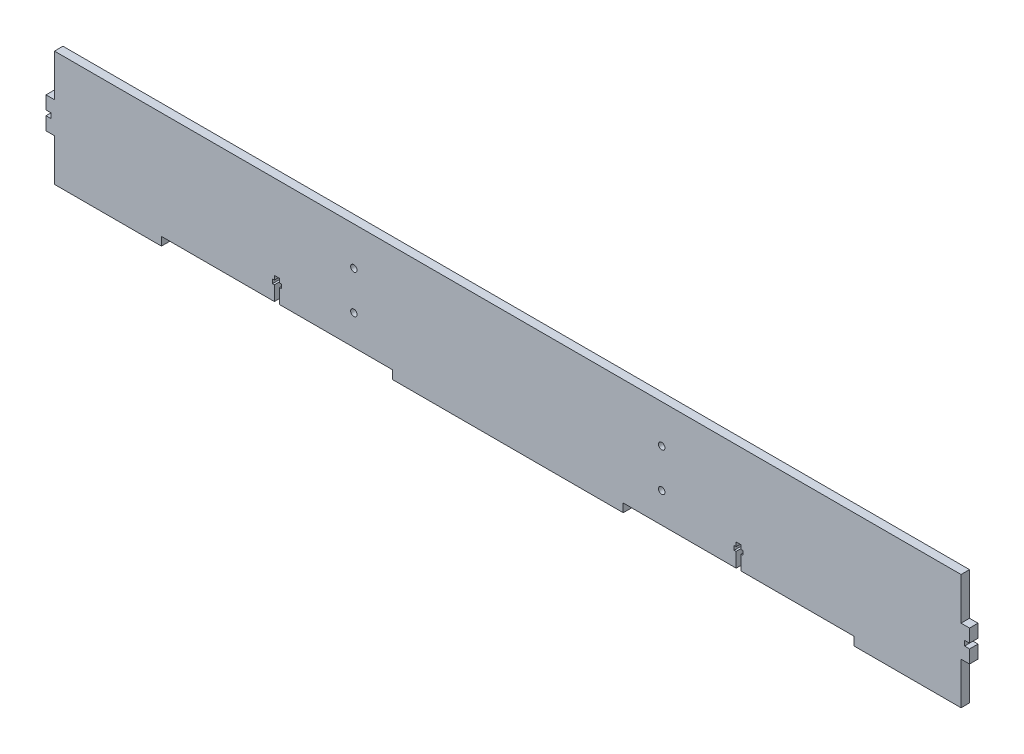
SolidWorks part; units mm, degrees
ref_plane "Front Plane" through (0, 0, 0) normal (0, 0, 1) x (1, 0, 0)
ref_plane "Top Plane" through (0, 0, 0) normal (0, 1, 0) x (1, 0, 0)
ref_plane "Right Plane" through (0, 0, 0) normal (1, 0, 0) x (0, 0, -1)
sketch "Sketch1" plane through (0, 0, 0) normal (0, 0, 1) x (1, 0, 0)
  line L0 (308.5, 78) -> (308.5, 50.625)
  line L1 (308.5, 50.625) -> (303, 50.625)
  line L2 (303, 50.625) -> (303, 42.125)
  line L3 (303, 42.125) -> (306.25, 42.125)
  line L4 (306.25, 42.125) -> (306.25, 40.5)
  line L5 (306.25, 40.5) -> (306.25, 38.875)
  line L6 (306.25, 38.875) -> (303, 38.875)
  line L7 (303, 38.875) -> (303, 30.375)
  line L8 (303, 30.375) -> (308.5, 30.375)
  line L9 (308.5, 30.375) -> (308.5, 3)
  line L10 (308.5, 3) -> (378, 3)
  line L11 (378, 3) -> (378, 8.5)
  line L12 (378, 8.5) -> (451.375, 8.5)
  line L13 (451.375, 8.5) -> (451.375, 17.95)
  line L14 (451.375, 17.95) -> (450.125, 17.95)
  line L15 (450.125, 17.95) -> (450.125, 20.6)
  line L16 (450.125, 20.6) -> (451.375, 20.6)
  line L17 (451.375, 20.6) -> (451.375, 23.25)
  line L18 (451.375, 23.25) -> (454.625, 23.25)
  line L19 (454.625, 23.25) -> (454.625, 20.6)
  line L20 (454.625, 20.6) -> (455.875, 20.6)
  line L21 (455.875, 20.6) -> (455.875, 17.95)
  line L22 (455.875, 17.95) -> (454.625, 17.95)
  line L23 (454.625, 17.95) -> (454.625, 8.5)
  line L24 (454.625, 8.5) -> (528, 8.5)
  line L25 (528, 8.5) -> (528, 3)
  line L26 (528, 3) -> (678, 3)
  line L27 (678, 3) -> (678, 8.5)
  line L28 (678, 8.5) -> (751.375, 8.5)
  line L29 (751.375, 8.5) -> (751.375, 17.95)
  line L30 (751.375, 17.95) -> (750.125, 17.95)
  line L31 (750.125, 17.95) -> (750.125, 20.6)
  line L32 (750.125, 20.6) -> (751.375, 20.6)
  line L33 (751.375, 20.6) -> (751.375, 23.25)
  line L34 (751.375, 23.25) -> (754.625, 23.25)
  line L35 (754.625, 23.25) -> (754.625, 20.6)
  line L36 (754.625, 20.6) -> (755.875, 20.6)
  line L37 (755.875, 20.6) -> (755.875, 17.95)
  line L38 (755.875, 17.95) -> (754.625, 17.95)
  line L39 (754.625, 17.95) -> (754.625, 8.5)
  line L40 (754.625, 8.5) -> (828, 8.5)
  line L41 (828, 8.5) -> (828, 3)
  line L42 (828, 3) -> (897.5, 3)
  line L43 (897.5, 3) -> (897.5, 30.375)
  line L44 (897.5, 30.375) -> (903, 30.375)
  line L45 (903, 30.375) -> (903, 38.875)
  line L46 (903, 38.875) -> (899.75, 38.875)
  line L47 (899.75, 38.875) -> (899.75, 40.5)
  line L48 (899.75, 40.5) -> (899.75, 42.125)
  line L49 (899.75, 42.125) -> (903, 42.125)
  line L50 (903, 42.125) -> (903, 50.625)
  line L51 (903, 50.625) -> (897.5, 50.625)
  line L52 (897.5, 50.625) -> (897.5, 78)
  line L53 (897.5, 78) -> (308.5, 78)
extrude "Boss-Extrude1" add sketch "Sketch1" along normal blind 5.5
sketch "Sketch2" plane through (0, 0, 5.5) normal (0, 0, 1) x (1, 0, 0)
  line L0 (897.5, 78) -> (308.5, 78) construction
  line L1 (503, 53) -> (703, 53)
  line L2 (503, 53) -> (503, 28)
  line L3 (503, 28) -> (703, 28)
  line L4 (703, 53) -> (703, 28)
  circle A0 centre (503, 53) radius 2.1
  circle A1 centre (503, 28) radius 2.1
  circle A2 centre (703, 28) radius 2.1
  circle A3 centre (703, 53) radius 2.1
  point P4 (603, 53)
  point P7 (603, 78)
  dimension "D4" = 4.2
  dimension "D1" = 25
  dimension "D2" = 200
  dimension "D3" = 25
extrude "Cut-Extrude1" cut sketch "Sketch2" against normal through all contours A0 | A1 | A2 | A3
